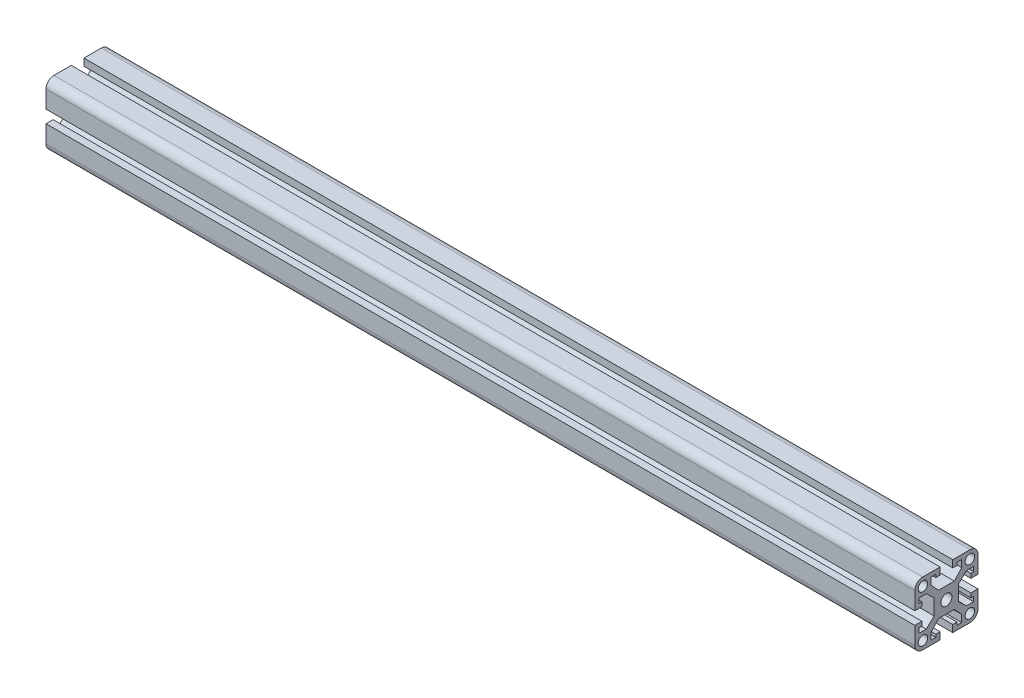
SolidWorks part; units mm, degrees
ref_plane "前视基准面" through (0, 0, 0) normal (0, 0, 1) x (1, 0, 0)
ref_plane "上视基准面" through (0, 0, 0) normal (0, 1, 0) x (1, 0, 0)
ref_plane "右视基准面" through (0, 0, 0) normal (1, 0, 0) x (0, 0, -1)
other "Configuration Table"
sketch "草图1" plane through (0, 0, 0) normal (1, 0, 0) x (0, 0, -1)
  line L1 (20.705, 55.0358) -> (60.705, 55.0358)
  line L2 (20.705, 55.0358) -> (20.705, 15.0358)
  line L3 (20.705, 15.0358) -> (60.705, 15.0358)
  line L4 (60.705, 55.0358) -> (60.705, 15.0358)
  dimension "D1" = 40
  dimension "D2" = 40
extrude "凸台-拉伸1" add sketch "草图1" along normal blind 550
sketch "草图2" plane through (550, 0, 0) normal (1, 0, 0) x (0, 0, -1)
  line L0 (40.705, 55.0358) -> (40.705, 15.0358) construction
  line L1 (60.705, 55.0358) -> (20.705, 55.0358) construction
  line L2 (20.705, 15.0358) -> (60.705, 15.0358) construction
  line L3 (20.705, 35.0358) -> (60.705, 35.0358) construction
  line L4 (20.705, 55.0358) -> (20.705, 15.0358) construction
  line L5 (60.705, 15.0358) -> (60.705, 55.0358) construction
  line L6 (36.705, 15.0358) -> (36.705, 19.5358)
  line L7 (36.705, 15.0358) -> (44.705, 15.0358)
  line L8 (36.705, 19.5358) -> (34.005, 19.5358)
  line L9 (34.005, 19.5358) -> (34.005, 17.7358)
  line L10 (34.005, 17.7358) -> (31.005, 17.7358)
  line L11 (31.005, 17.7358) -> (31.005, 22.2358)
  line L12 (45.705, 27.2758) -> (35.705, 27.2758)
  line L13 (31.005, 22.2358) -> (35.705, 27.2758)
  line L14 (50.405, 22.2358) -> (45.705, 27.2758)
  line L15 (50.405, 17.7358) -> (50.405, 22.2358)
  line L16 (47.405, 17.7358) -> (50.405, 17.7358)
  line L17 (47.405, 19.5358) -> (47.405, 17.7358)
  line L18 (44.705, 19.5358) -> (47.405, 19.5358)
  line L19 (44.705, 15.0358) -> (44.705, 19.5358)
  line L20 (44.705, 55.0358) -> (44.705, 50.5358)
  line L21 (44.705, 50.5358) -> (47.405, 50.5358)
  line L22 (47.405, 50.5358) -> (47.405, 52.3358)
  line L23 (47.405, 52.3358) -> (50.405, 52.3358)
  line L24 (50.405, 52.3358) -> (50.405, 47.8358)
  line L25 (50.405, 47.8358) -> (45.705, 42.7958)
  line L26 (31.005, 47.8358) -> (35.705, 42.7958)
  line L27 (45.705, 42.7958) -> (35.705, 42.7958)
  line L28 (31.005, 52.3358) -> (31.005, 47.8358)
  line L29 (34.005, 52.3358) -> (31.005, 52.3358)
  line L30 (34.005, 50.5358) -> (34.005, 52.3358)
  line L31 (36.705, 50.5358) -> (34.005, 50.5358)
  line L32 (36.705, 55.0358) -> (44.705, 55.0358)
  line L33 (36.705, 55.0358) -> (36.705, 50.5358)
  line L62 (20.705, 31.0358) -> (20.705, 39.0358)
  line L63 (20.705, 39.0358) -> (25.205, 39.0358)
  line L64 (25.205, 39.0358) -> (25.205, 41.7358)
  line L65 (25.205, 41.7358) -> (23.405, 41.7358)
  line L66 (23.405, 41.7358) -> (23.405, 44.7358)
  line L67 (23.405, 44.7358) -> (27.955, 44.7358)
  line L68 (32.945, 30.0358) -> (32.945, 40.0358)
  line L69 (32.945, 40.0358) -> (27.955, 44.7358)
  line L70 (32.945, 30.0358) -> (27.955, 25.3358)
  line L71 (23.405, 25.3358) -> (27.955, 25.3358)
  line L72 (23.405, 28.3358) -> (23.405, 25.3358)
  line L73 (25.205, 28.3358) -> (23.405, 28.3358)
  line L74 (25.205, 31.0358) -> (25.205, 28.3358)
  line L75 (20.705, 31.0358) -> (25.205, 31.0358)
  line L76 (60.705, 31.0358) -> (56.205, 31.0358)
  line L77 (56.205, 31.0358) -> (56.205, 28.3358)
  line L78 (56.205, 28.3358) -> (58.005, 28.3358)
  line L79 (58.005, 28.3358) -> (58.005, 25.3358)
  line L80 (58.005, 25.3358) -> (53.455, 25.3358)
  line L81 (48.465, 30.0358) -> (53.455, 25.3358)
  line L82 (48.465, 40.0358) -> (53.455, 44.7358)
  line L83 (48.465, 30.0358) -> (48.465, 40.0358)
  line L84 (58.005, 44.7358) -> (53.455, 44.7358)
  line L85 (58.005, 41.7358) -> (58.005, 44.7358)
  line L86 (56.205, 41.7358) -> (58.005, 41.7358)
  line L87 (56.205, 39.0358) -> (56.205, 41.7358)
  line L88 (60.705, 39.0358) -> (56.205, 39.0358)
  line L89 (60.705, 31.0358) -> (60.705, 39.0358)
  line L90 (31.005, 47.8358) -> (31.005, 44.7358) construction
  line L91 (31.005, 44.7358) -> (27.955, 44.7358) construction
  line L92 (31.005, 52.3358) -> (31.005, 55.0358) construction
  circle A0 centre (40.705, 35.0358) radius 3.5
  circle A1 centre (25.855, 49.8858) radius 3
  circle A2 centre (25.855, 20.1858) radius 3
  circle A3 centre (55.555, 49.8858) radius 3
  circle A4 centre (55.555, 20.1858) radius 3
  point P22 (40.705, 27.2758)
  point P41 (40.705, 42.7958)
  point P52 (32.945, 35.0358)
  point P71 (48.465, 35.0358)
  dimension "D17" = 7
  dimension "D20" = 6
  dimension "D1" = 4
  dimension "D2" = 2.7
  dimension "D3" = 4.5
  dimension "D4" = 2.7
  dimension "D5" = 3
  dimension "D6" = 4.5
  dimension "D7" = 12.24
  dimension "D8" = 5
  dimension "D9" = 4
  dimension "D10" = 2.7
  dimension "D11" = 3
  dimension "D12" = 4.5
  dimension "D13" = 2.7
  dimension "D14" = 4.55
  dimension "D15" = 12.24
  dimension "D16" = 5
  dimension "D18" = 5.15
  dimension "D19" = 5.15
extrude "切除-拉伸1" cut sketch "草图2" against normal up to next
fillet "圆角1" radius 5 4 edges at (275, 15.0358, -20.705) (275, 15.0358, -60.705) (275, 55.0358, -60.705) (275, 55.0358, -20.705)
